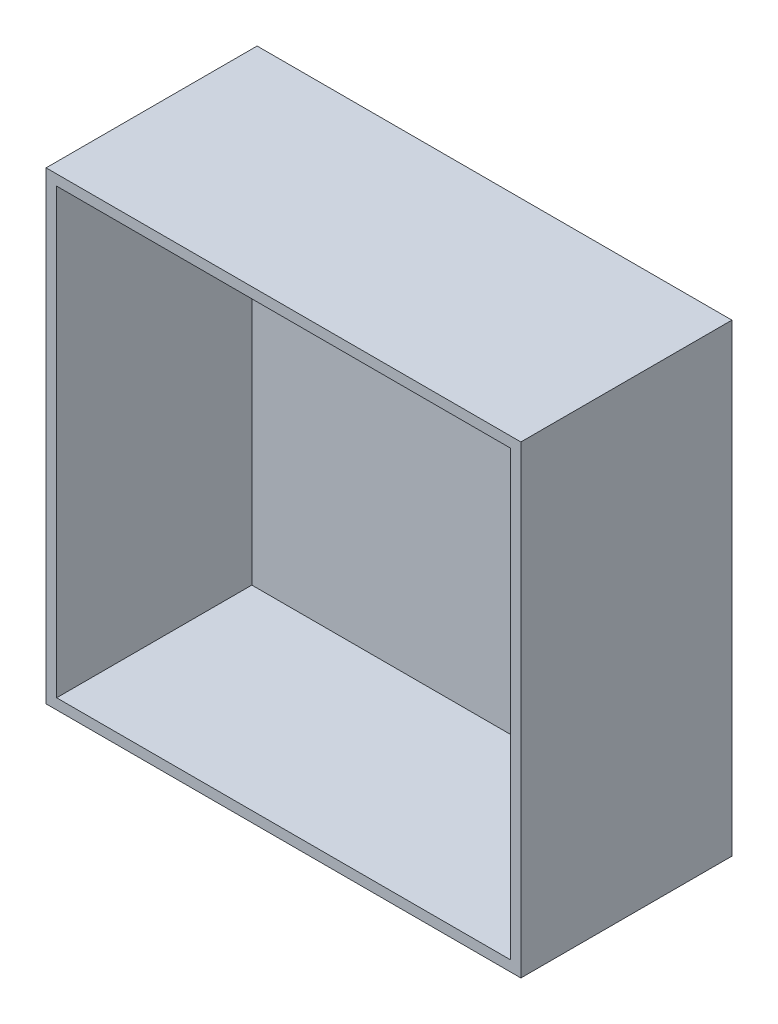
SolidWorks part; units mm, degrees
ref_plane "前视基准面" through (0, 0, 0) normal (0, 0, 1) x (1, 0, 0)
ref_plane "上视基准面" through (0, 0, 0) normal (0, 1, 0) x (1, 0, 0)
ref_plane "右视基准面" through (0, 0, 0) normal (1, 0, 0) x (0, 0, -1)
other "Configuration Table"
sketch "草图1" plane through (0, 0, 0) normal (0, 0, 1) x (1, 0, 0)
  line L1 (120, -44) -> (210, -44)
  line L2 (120, -44) -> (120, 44)
  line L3 (120, 44) -> (210, 44)
  line L4 (210, -44) -> (210, 44)
  dimension "D1" = 90
  dimension "D2" = 88
extrude "Tray" add sketch "草图1" along normal blind 40 separate body
sketch "草图2" plane through (0, 0, 0) normal (0, 0, 1) x (1, 0, 0)
  line L1 (122, -42) -> (208, -42)
  line L2 (122, -42) -> (122, 42)
  line L3 (122, 42) -> (208, 42)
  line L4 (208, -42) -> (208, 42)
  dimension "D1" = 86
  dimension "D2" = 84
extrude "TrayCavity" cut sketch "草图2" along normal blind 37 from offset 3
